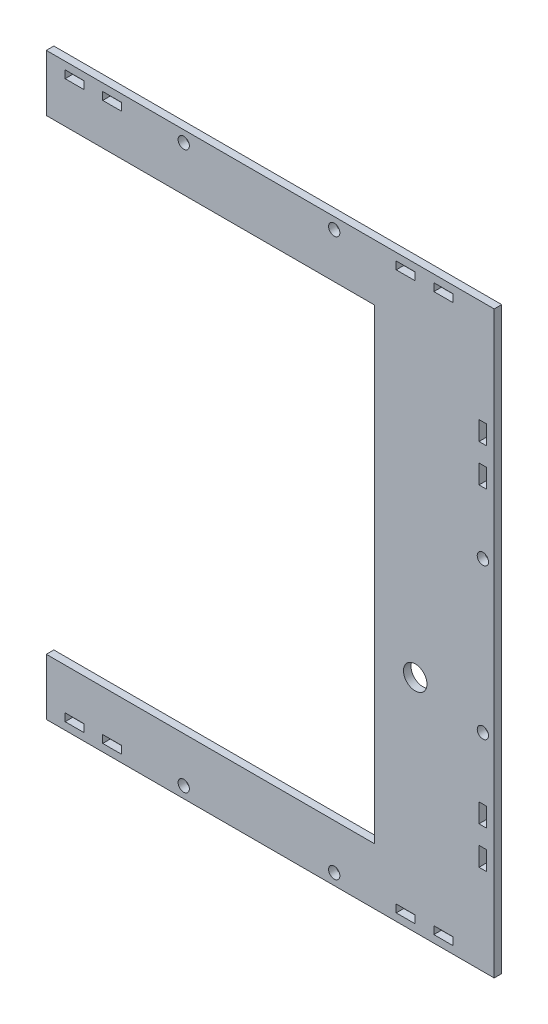
SolidWorks part; units mm, degrees
ref_plane "前视基准面" through (0, 0, 0) normal (0, 0, 1) x (1, 0, 0)
ref_plane "上视基准面" through (0, 0, 0) normal (0, 1, 0) x (1, 0, 0)
ref_plane "右视基准面" through (0, 0, 0) normal (1, 0, 0) x (0, 0, -1)
sketch "草图1" plane through (0, 0, 0) normal (0, 0, 1) x (1, 0, 0)
  line L0 (-46.0613, -2.3972) -> (-51.1113, -0.3472) construction
  line L5 (36.8887, -0.3472) -> (41.9387, -0.3472)
  line L6 (36.8887, -0.3472) -> (36.8887, -2.3972)
  line L11 (36.8887, -2.3972) -> (41.9387, -2.3972)
  line L12 (41.9387, -0.3472) -> (41.9387, -2.3972)
  line L13 (36.8887, -0.3472) -> (41.9387, -2.3972) construction
  line L14 (36.8887, -2.3972) -> (41.9387, -0.3472) construction
  line L15 (46.8887, -0.3472) -> (51.9387, -0.3472)
  line L25 (46.8887, -0.3472) -> (46.8887, -2.3972)
  line L30 (46.8887, -2.3972) -> (51.9387, -2.3972)
  line L31 (51.9387, -0.3472) -> (51.9387, -2.3972)
  line L36 (46.8887, -0.3472) -> (51.9387, -2.3972) construction
  line L37 (46.8887, -2.3972) -> (51.9387, -0.3472) construction
  line L38 (-46.0613, -0.3472) -> (-51.1113, -2.3972) construction
  line L39 (-36.0613, -2.3972) -> (-41.1113, -0.3472) construction
  line L40 (-36.0613, -0.3472) -> (-41.1113, -2.3972) construction
  line L55 (-51.1113, -0.3472) -> (-51.1113, -2.3972)
  line L60 (-46.0613, -2.3972) -> (-51.1113, -2.3972)
  line L61 (-46.0613, -0.3472) -> (-46.0613, -2.3972)
  line L66 (-46.0613, -0.3472) -> (-51.1113, -0.3472)
  line L67 (-41.1113, -0.3472) -> (-41.1113, -2.3972)
  line L68 (-36.0613, -2.3972) -> (-41.1113, -2.3972)
  line L69 (-36.0613, -0.3472) -> (-36.0613, -2.3972)
  line L70 (-36.0613, -0.3472) -> (-41.1113, -0.3472)
  line L81 (-48.5863, -1.3722) -> (49.4137, -1.3722) construction
  line L82 (-19.5863, -149.3722) -> (-8.6103, -149.3722) construction
  line L83 (-46.0613, -150.3972) -> (-51.1113, -148.3472) construction
  line L84 (36.8887, -148.3472) -> (41.9387, -148.3472)
  line L85 (36.8887, -148.3472) -> (36.8887, -150.3972)
  line L86 (36.8887, -150.3972) -> (41.9387, -150.3972)
  line L87 (41.9387, -148.3472) -> (41.9387, -150.3972)
  line L88 (36.8887, -148.3472) -> (41.9387, -150.3972) construction
  line L89 (36.8887, -150.3972) -> (41.9387, -148.3472) construction
  line L90 (46.8887, -148.3472) -> (51.9387, -148.3472)
  line L91 (46.8887, -148.3472) -> (46.8887, -150.3972)
  line L92 (46.8887, -150.3972) -> (51.9387, -150.3972)
  line L93 (51.9387, -148.3472) -> (51.9387, -150.3972)
  line L94 (46.8887, -148.3472) -> (51.9387, -150.3972) construction
  line L95 (46.8887, -150.3972) -> (51.9387, -148.3472) construction
  line L96 (-46.0613, -148.3472) -> (-51.1113, -150.3972) construction
  line L97 (-36.0613, -150.3972) -> (-41.1113, -148.3472) construction
  line L98 (-36.0613, -148.3472) -> (-41.1113, -150.3972) construction
  line L99 (-51.1113, -148.3472) -> (-51.1113, -150.3972)
  line L100 (-46.0613, -150.3972) -> (-51.1113, -150.3972)
  line L101 (-46.0613, -148.3472) -> (-46.0613, -150.3972)
  line L102 (-46.0613, -148.3472) -> (-51.1113, -148.3472)
  line L103 (-41.1113, -148.3472) -> (-41.1113, -150.3972)
  line L104 (-36.0613, -150.3972) -> (-41.1113, -150.3972)
  line L105 (-36.0613, -148.3472) -> (-36.0613, -150.3972)
  line L106 (-36.0613, -148.3472) -> (-41.1113, -148.3472)
  line L107 (59.9198, -57.3722) -> (59.9198, -97.3722) construction
  line L108 (-56.1113, -13.3722) -> (31.071, -13.3722)
  line L109 (-56.1113, 1.6278) -> (62.9198, 1.6278)
  line L110 (-56.1113, 1.6278) -> (-56.1113, -152.3722) construction
  line L111 (-56.1113, -152.3722) -> (62.9198, -152.3722) construction
  line L112 (62.9198, 1.6278) -> (62.9198, -152.3722)
  line L113 (60.9448, -123.8472) -> (58.8948, -128.8972) construction
  line L114 (58.8948, -40.8972) -> (58.8948, -35.8472)
  line L115 (58.8948, -40.8972) -> (60.9448, -40.8972)
  line L116 (60.9448, -40.8972) -> (60.9448, -35.8472)
  line L117 (58.8948, -35.8472) -> (60.9448, -35.8472)
  line L118 (58.8948, -40.8972) -> (60.9448, -35.8472) construction
  line L119 (60.9448, -40.8972) -> (58.8948, -35.8472) construction
  line L120 (58.8948, -30.8972) -> (58.8948, -25.8472)
  line L121 (58.8948, -30.8972) -> (60.9448, -30.8972)
  line L122 (60.9448, -30.8972) -> (60.9448, -25.8472)
  line L123 (58.8948, -25.8472) -> (60.9448, -25.8472)
  line L124 (58.8948, -30.8972) -> (60.9448, -25.8472) construction
  line L125 (60.9448, -30.8972) -> (58.8948, -25.8472) construction
  line L126 (58.8948, -123.8472) -> (60.9448, -128.8972) construction
  line L127 (60.9448, -113.8472) -> (58.8948, -118.8972) construction
  line L128 (58.8948, -113.8472) -> (60.9448, -118.8972) construction
  line L129 (58.8948, -128.8972) -> (60.9448, -128.8972)
  line L130 (60.9448, -123.8472) -> (60.9448, -128.8972)
  line L131 (58.8948, -123.8472) -> (60.9448, -123.8472)
  line L132 (58.8948, -123.8472) -> (58.8948, -128.8972)
  line L133 (58.8948, -118.8972) -> (60.9448, -118.8972)
  line L134 (60.9448, -113.8472) -> (60.9448, -118.8972)
  line L135 (58.8948, -113.8472) -> (60.9448, -113.8472)
  line L136 (58.8948, -113.8472) -> (58.8948, -118.8972)
  line L137 (31.071, -13.3722) -> (31.071, -137.3722)
  line L138 (31.071, -137.3722) -> (-56.1113, -137.3722)
  line L139 (-56.1113, -137.3722) -> (-56.1113, -152.3722)
  line L140 (-56.1113, -13.3722) -> (-56.1113, 1.6278)
  line L141 (20.4137, -149.3722) -> (20.4137, -224.3722) construction
  line L142 (62.9198, -152.3722) -> (-56.1113, -152.3722)
  line L144 (36.8887, -223.3472) -> (41.9387, -223.3472) construction
  line L145 (36.8887, -223.3472) -> (36.8887, -225.3972) construction
  line L146 (36.8887, -225.3972) -> (41.9387, -225.3972) construction
  line L147 (41.9387, -223.3472) -> (41.9387, -225.3972) construction
  line L150 (46.8887, -223.3472) -> (51.9387, -223.3472) construction
  line L151 (46.8887, -223.3472) -> (46.8887, -225.3972) construction
  line L152 (46.8887, -225.3972) -> (51.9387, -225.3972) construction
  line L153 (51.9387, -223.3472) -> (51.9387, -225.3972) construction
  line L159 (-51.1113, -223.3472) -> (-51.1113, -225.3972) construction
  line L160 (-46.0613, -225.3972) -> (-51.1113, -225.3972) construction
  line L161 (-46.0613, -223.3472) -> (-46.0613, -225.3972) construction
  line L162 (-46.0613, -223.3472) -> (-51.1113, -223.3472) construction
  line L163 (-41.1113, -223.3472) -> (-41.1113, -225.3972) construction
  line L164 (-36.0613, -225.3972) -> (-41.1113, -225.3972) construction
  line L165 (-36.0613, -223.3472) -> (-36.0613, -225.3972) construction
  line L166 (-36.0613, -223.3472) -> (-41.1113, -223.3472) construction
  line L167 (-56.1113, -152.3722) -> (-56.1113, -227.3972) construction
  line L168 (-56.1113, -227.3972) -> (62.9198, -227.3972) construction
  line L169 (62.9198, -227.3972) -> (62.9198, -152.3722) construction
  circle A6 centre (-19.5863, -1.3722) radius 1.5
  circle A7 centre (20.4137, -1.3722) radius 1.5
  circle A9 centre (-19.5863, -149.3722) radius 1.5
  circle A10 centre (20.4137, -149.3722) radius 1.5
  circle A11 centre (59.9198, -97.3722) radius 1.5
  circle A12 centre (59.9198, -57.3722) radius 1.5
  circle A13 centre (41.9387, -93.6781) radius 3.1213
  circle A14 centre (-19.5863, -224.3722) radius 1.5 construction
  circle A15 centre (20.4137, -224.3722) radius 1.5 construction
  point P8 (-38.5863, -1.3722)
  point P13 (39.4137, -1.3722)
  point P35 (-38.5863, -149.3722)
  point P40 (39.4137, -149.3722)
  point P54 (3.4042, -152.3722)
  point P80 (101.1063, -340.4435)
  point P91 (-38.5863, -224.3722)
  point P96 (39.4137, -224.3722)
  dimension "D1" = 148
  dimension "D2" = 3
  dimension "D4" = 3
  dimension "D5" = 5
  dimension "D6" = 15
  dimension "D7" = 15
extrude "凸台-拉伸1" add sketch "草图1" along normal blind 2
